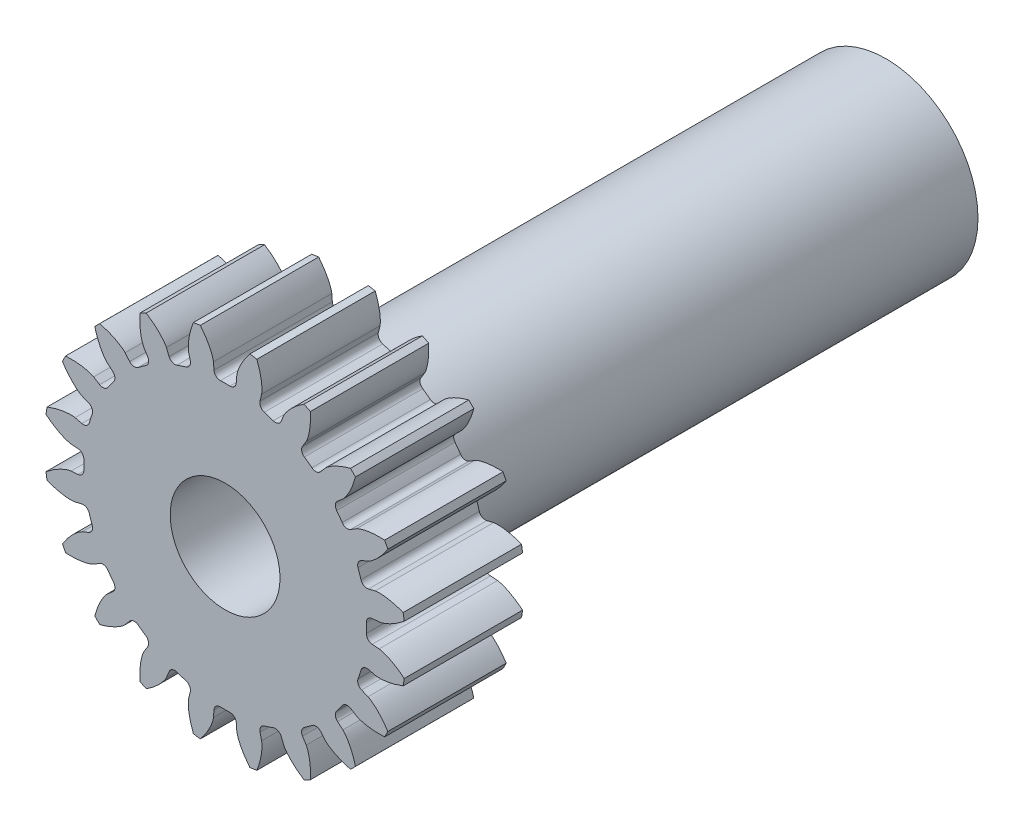
SolidWorks part; units mm, degrees
ref_plane "Front Plane" through (0, 0, 0) normal (0, 0, 1) x (1, 0, 0)
ref_plane "Top Plane" through (0, 0, 0) normal (0, 1, 0) x (1, 0, 0)
ref_plane "Right Plane" through (0, 0, 0) normal (1, 0, 0) x (0, 0, -1)
ref_axis "Gear Axis" through (0, 0, -43.7625) along (0, 0, 1)
sketch "Blank Sketch" plane through (0, 0, 0) normal (0, 0, 1) x (1, 0, 0)
  circle A0 centre (0, 0) radius 13.75
  dimension "OD" = 27.5
extrude "Blank" add sketch "Blank Sketch" along normal blind 9
sketch "Tooth Space Sketch" plane through (0, 0, 0) normal (0, 0, 1) x (1, 0, 0)
  line L0 (11.7126, 0.8876) -> (11.1829, 0.8474)
  line L1 (11.7126, -0.8876) -> (11.1829, -0.8474)
  line L2 (14.705, 2.9601) -> (14.705, -2.9601)
  arc A0 (11.1829, 0.8474) -> (10.744, 0.358) centre (11.2188, 0.3738) ccw
  arc A1 (10.744, -0.358) -> (11.1829, -0.8474) centre (11.2188, -0.3738) ccw
  arc A2 (10.744, -0.358) -> (10.744, 0.358) centre (0, 0) ccw
  spline S0 degree 4 poles (11.7126, 0.8876) (11.718, 0.8881) (11.7333, 0.8898) (11.7621, 0.8941) (11.8087, 0.9028) (11.8679, 0.9161) (11.9438, 0.936) (12.0325, 0.9629) (12.1291, 0.9959) (12.2333, 1.0356) (12.3362, 1.0785) (12.4379, 1.1244) (12.5383, 1.1729) (12.6587, 1.2348) (12.8015, 1.3135) (12.9658, 1.4118) (13.1489, 1.5308) (13.3319, 1.66) (13.5089, 1.7935) (13.6838, 1.9356) (13.8504, 2.0781) (14.0193, 2.2333) (14.173, 2.3803) (14.3404, 2.5526) (14.474, 2.694) (14.6449, 2.8885) (14.7442, 3.0057) (14.8584, 3.1456) (14.9081, 3.2092) (14.9387, 3.2482) knots 0 0 0 0 0 0.005377 0.015084 0.028532 0.04661 0.064855 0.092111 0.119476 0.146842 0.174209 0.201575 0.228941 0.256307 0.307035 0.361767 0.4165 0.471232 0.525964 0.580697 0.635429 0.690161 0.744894 0.799626 0.854358 0.909091 0.954545 1 1 1 1 1 construction
  spline S1 degree 4 poles (11.7126, 0.8876) (11.718, 0.8881) (11.7333, 0.8898) (11.7621, 0.8941) (11.8087, 0.9028) (11.8679, 0.9161) (11.9438, 0.936) (12.0325, 0.9629) (12.1291, 0.9959) (12.2333, 1.0356) (12.3362, 1.0785) (12.4379, 1.1244) (12.5383, 1.1729) (12.6587, 1.2348) (12.8015, 1.3135) (12.9658, 1.4118) (13.1489, 1.5308) (13.3319, 1.66) (13.5089, 1.7935) (13.6838, 1.9356) (13.8504, 2.0781) (14.0193, 2.2333) (14.173, 2.3803) (14.3404, 2.5526) (14.474, 2.694) (14.6078, 2.8463) (14.6723, 2.9214) (14.705, 2.9601) knots 0 0 0 0 0 0.005377 0.015084 0.028532 0.04661 0.064855 0.092111 0.119476 0.146842 0.174209 0.201575 0.228941 0.256307 0.307035 0.361767 0.4165 0.471232 0.525964 0.580697 0.635429 0.690161 0.744894 0.799626 0.854358 0.909091 0.909091 0.909091 0.909091 0.909091
  spline S2 degree 4 poles (11.7126, -0.8876) (11.718, -0.8881) (11.7333, -0.8898) (11.7621, -0.8941) (11.8087, -0.9028) (11.8679, -0.9161) (11.9438, -0.936) (12.0325, -0.9629) (12.1291, -0.9959) (12.2333, -1.0356) (12.3362, -1.0785) (12.4379, -1.1244) (12.5383, -1.1729) (12.6587, -1.2348) (12.8015, -1.3135) (12.9658, -1.4118) (13.1489, -1.5308) (13.3319, -1.66) (13.5089, -1.7935) (13.6838, -1.9356) (13.8504, -2.0781) (14.0193, -2.2333) (14.173, -2.3803) (14.3404, -2.5526) (14.474, -2.694) (14.6449, -2.8885) (14.7442, -3.0057) (14.8584, -3.1456) (14.9081, -3.2092) (14.9387, -3.2482) knots 0 0 0 0 0 0.005377 0.015084 0.028532 0.04661 0.064855 0.092111 0.119476 0.146842 0.174209 0.201575 0.228941 0.256307 0.307035 0.361767 0.4165 0.471232 0.525964 0.580697 0.635429 0.690161 0.744894 0.799626 0.854358 0.909091 0.954545 1 1 1 1 1 construction
  spline S3 degree 4 poles (11.7126, -0.8876) (11.718, -0.8881) (11.7333, -0.8898) (11.7621, -0.8941) (11.8087, -0.9028) (11.8679, -0.9161) (11.9438, -0.936) (12.0325, -0.9629) (12.1291, -0.9959) (12.2333, -1.0356) (12.3362, -1.0785) (12.4379, -1.1244) (12.5383, -1.1729) (12.6587, -1.2348) (12.8015, -1.3135) (12.9658, -1.4118) (13.1489, -1.5308) (13.3319, -1.66) (13.5089, -1.7935) (13.6838, -1.9356) (13.8504, -2.0781) (14.0193, -2.2333) (14.173, -2.3803) (14.3404, -2.5526) (14.474, -2.694) (14.6078, -2.8463) (14.6723, -2.9214) (14.705, -2.9601) knots 0 0 0 0 0 0.005377 0.015084 0.028532 0.04661 0.064855 0.092111 0.119476 0.146842 0.174209 0.201575 0.228941 0.256307 0.307035 0.361767 0.4165 0.471232 0.525964 0.580697 0.635429 0.690161 0.744894 0.799626 0.854358 0.909091 0.909091 0.909091 0.909091 0.909091
  dimension "Root" = 10.75
  dimension "Fillet" = 0.475
extrude "Tooth Space" cut sketch "Tooth Space Sketch" against normal through all both and the other way through all both
pattern_circular "Teeth" count 20 over 360 about axis through (0, 0, -43.7625) along (0, 0, 1) of "Tooth Space"
sketch "Bore Sketch" plane through (0, 0, 0) normal (0, 0, 1) x (1, 0, 0)
  circle A0 centre (0, 0) radius 4.175
  dimension "Bore" = 8.35
extrude "Bore" cut sketch "Bore Sketch" against normal through all both and the other way through all both
sketch "Sketch1" plane through (0, 0, 9) normal (0, 0, 1) x (1, 0, 0)
  circle A0 centre (0, 0) radius 4.175 construction
  circle A1 centre (0, 0) radius 4.175
  circle A4 centre (0, 0) radius 7
  dimension "D1" = 14
extrude "Boss-Extrude1" add sketch "Sketch1" against normal blind 50.25
equation "\"No. of Teeth\"= 20"
equation "\"Module\"= 1.25"
equation "\"Bore Diameter\"= 8.35"
equation "\"Pressure Angle\"= 20"
equation "\"Outer Diameter\"= ( \"No. of Teeth\" + 2 ) * \"Module\""
equation "\"Pitch Diameter\"= \"No. of Teeth\" * \"Module\""
equation "\"Backlash\"= IIF ( \"Module\" <= 1 , 0.3 * \"Module\" , 0.3 )"
equation "\"Arc Length\"= ( ( \"Module\" * pi ) / 2 + \"Backlash\" )"
equation "\"Fillet Radius\"= 0.38 * \"Module\""
equation "\"Tooth Depth\"= IIF ( \"Module\" <= 1.25 , \"Module\" * 2.4 , \"Module\" * 2.25 )"
equation "\"Face Width\"= 9"
equation "\"Root Diameter\"= \"Outer Diameter\" - 2 * \"Tooth Depth\""
equation "\"Base Diameter\"= \"Pitch Diameter\" * cos ( \"Pressure Angle\" )"
equation "\"Base Radius\"= \"Base Diameter\" / 2"
equation "\"Tooth Thickness\"= \"Module\" * pi - \"Arc Length\""
equation "\"Half Space Angle\"= ( \"Arc Length\" / \"Pitch Diameter\" ) * 180 / pi"
equation "\"Involute Fn\"= tan ( \"Pressure Angle\" ) - \"Pressure Angle\" * pi / 180"
equation "\"Flank Offset\"= \"Arc Length\" / \"Pitch Diameter\" - \"Involute Fn\""
equation "\"Tip Cap Diameter\"= \"Outer Diameter\" + 2 * \"Module\""
equation "\"Flank Start Diameter\"= IIF ( \"Base Diameter\" >= ( \"Root Diameter\" + 3 * \"Fillet Radius\" ) , \"Base Diameter\" , \"Root Diameter\" + 3 * \"Fillet Radius\" )"
equation "\"Involute t1\"= ( abs ( ( \"Flank Start Diameter\" / \"Base Diameter\" ) ^ 2 - 1 ) ) ^ 0.5"
equation "\"Involute t2\"= ( abs ( ( \"Tip Cap Diameter\" / \"Base Diameter\" ) ^ 2 - 1 ) ) ^ 0.5"
equation "\"Flank Arc Radius\"= ( \"Pitch Diameter\" / 2 ) * sin ( \"Pressure Angle\" )"
equation "\"Flank Centre Angle\"= \"Half Space Angle\" + \"Pressure Angle\""
equation "\"OD@Blank Sketch\"= \"Outer Diameter\""
equation "\"Width@Blank\"= \"Face Width\""
equation "\"Root@Tooth Space Sketch\"= \"Root Diameter\" / 2"
equation "\"Fillet@Tooth Space Sketch\"= \"Fillet Radius\""
equation "\"Count@Teeth\"= \"No. of Teeth\""
equation "\"Bore@Bore Sketch\"= \"Bore Diameter\""
